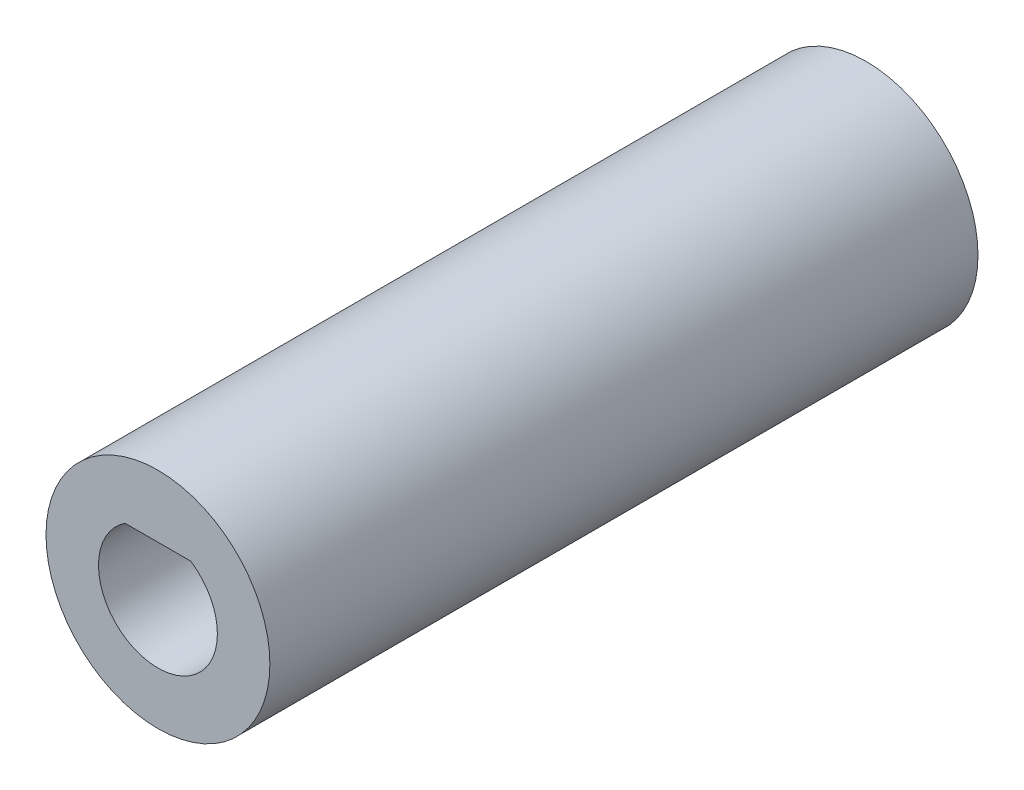
SolidWorks part; units mm, degrees
ref_plane "Front Plane" through (0, 0, 0) normal (0, 0, 1) x (1, 0, 0)
ref_plane "Top Plane" through (0, 0, 0) normal (0, 1, 0) x (1, 0, 0)
ref_plane "Right Plane" through (0, 0, 0) normal (1, 0, 0) x (0, 0, -1)
sketch "Sketch1" plane through (0, 0, 0) normal (0, 0, 1) x (1, 0, 0)
  circle A0 centre (0, 0) radius 3.65 construction
  circle A1 centre (0, 0) radius 5.65
  circle A2 centre (0, 0) radius 1.55
  circle A3 centre (0, 0) radius 3.65 construction
  arc A4 (-1.2776, -2.7957) -> (-1.2728, -2.7489) centre (-1.7505, -2.7239) ccw
  arc A5 (-0.4154, -3.0006) -> (-0.4367, -3.0426) centre (0, -3.2379) ccw
  arc A6 (0.4154, -3.0006) -> (-0.4154, -3.0006) centre (0, -3.2379) ccw
  arc A7 (0.4367, -3.0426) -> (0.4154, -3.0006) centre (0, -3.2379) ccw
  arc A8 (1.2728, -2.7489) -> (1.2776, -2.7957) centre (1.7505, -2.7239) ccw
  arc A9 (2.0123, -2.3235) -> (1.9717, -2.2997) centre (1.7505, -2.7239) ccw
  arc A10 (2.9491, -0.8667) -> (2.902, -0.8686) centre (2.9453, -1.3451) ccw
  arc A11 (2.5569, -1.6244) -> (2.5862, -1.6612) centre (2.9453, -1.3451) ccw
  arc A12 (3.0292, 0.0158) -> (3.0738, 0.0007) centre (3.2049, 0.4608) ccw
  arc A13 (2.9495, 0.8653) -> (2.911, 0.8382) centre (3.2049, 0.4608) ccw
  arc A14 (2.9491, -0.8667) -> (3.5766, -0.7323) centre (2.9608, 0.6111) ccw
  arc A15 (2.902, -0.8686) -> (2.5569, -1.6244) centre (2.9453, -1.3451) ccw
  arc A16 (2.8956, -2.2234) -> (2.5862, -1.6612) centre (1.4771, -2.6378) ccw
  arc A17 (2.6129, -2.5497) -> (2.8956, -2.2234) centre (0, 0) ccw
  arc A18 (2.0123, -2.3235) -> (2.6129, -2.5497) centre (2.8211, -1.0866) ccw
  arc A19 (1.9717, -2.2997) -> (1.2728, -2.7489) centre (1.7505, -2.7239) ccw
  arc A20 (1.2339, -3.436) -> (1.2776, -2.7957) centre (-0.1835, -3.0176) ccw
  arc A21 (0.8196, -3.5576) -> (1.2339, -3.436) centre (0, 0) ccw
  arc A22 (0.4367, -3.0426) -> (0.8196, -3.5576) centre (1.7858, -2.4394) ccw
  arc A23 (-0.8196, -3.5576) -> (-0.4367, -3.0426) centre (-1.7858, -2.4394) ccw
  arc A24 (-1.2339, -3.436) -> (-0.8196, -3.5576) centre (0, 0) ccw
  arc A25 (-1.2776, -2.7957) -> (-1.2339, -3.436) centre (0.1835, -3.0176) ccw
  arc A26 (3.5766, -0.7323) -> (3.638, -0.305) centre (0, 0) ccw
  arc A27 (3.638, -0.305) -> (3.0738, 0.0007) centre (2.6687, -1.4205) ccw
  arc A28 (2.911, 0.8382) -> (3.0292, 0.0158) centre (3.2049, 0.4608) ccw
  arc A29 (2.9495, 0.8653) -> (3.4047, 1.3176) centre (2.1604, 2.1148) ccw
  arc A30 (3.4047, 1.3176) -> (3.2254, 1.7103) centre (0, 0) ccw
  arc A31 (-1.9717, -2.2997) -> (-2.0123, -2.3235) centre (-1.7505, -2.7239) ccw
  arc A32 (-2.5862, -1.6612) -> (-2.5569, -1.6244) centre (-2.9453, -1.3451) ccw
  arc A33 (-2.902, -0.8686) -> (-2.9491, -0.8667) centre (-2.9453, -1.3451) ccw
  arc A34 (-3.0738, 0.0007) -> (-3.0292, 0.0158) centre (-3.2049, 0.4608) ccw
  arc A35 (-2.911, 0.8382) -> (-2.9495, 0.8653) centre (-3.2049, 0.4608) ccw
  arc A36 (-1.2728, -2.7489) -> (-1.9717, -2.2997) centre (-1.7505, -2.7239) ccw
  arc A37 (-2.6129, -2.5497) -> (-2.0123, -2.3235) centre (-2.8211, -1.0866) ccw
  arc A38 (-2.8956, -2.2234) -> (-2.6129, -2.5497) centre (0, 0) ccw
  arc A39 (-2.5862, -1.6612) -> (-2.8956, -2.2234) centre (-1.4771, -2.6378) ccw
  arc A40 (-2.5569, -1.6244) -> (-2.902, -0.8686) centre (-2.9453, -1.3451) ccw
  arc A41 (-3.5766, -0.7323) -> (-2.9491, -0.8667) centre (-2.9608, 0.6111) ccw
  arc A42 (-3.638, -0.305) -> (-3.5766, -0.7323) centre (0, 0) ccw
  arc A43 (-3.0738, 0.0007) -> (-3.638, -0.305) centre (-2.6687, -1.4205) ccw
  arc A44 (-3.0292, 0.0158) -> (-2.911, 0.8382) centre (-3.2049, 0.4608) ccw
  arc A45 (-3.4047, 1.3176) -> (-2.9495, 0.8653) centre (-2.1604, 2.1148) ccw
  arc A46 (-2.5854, 1.6624) -> (-2.5398, 1.651) centre (-2.447, 2.1203) ccw
  arc A47 (-1.9957, 2.279) -> (-2.0134, 2.3225) centre (-2.447, 2.1203) ccw
  arc A48 (-1.2762, 2.7963) -> (-1.244, 2.762) centre (-0.9122, 3.1067) ccw
  arc A49 (-0.4468, 2.9961) -> (-0.4382, 3.0424) centre (-0.9122, 3.1067) ccw
  arc A50 (2.5398, 1.651) -> (2.5854, 1.6624) centre (2.447, 2.1203) ccw
  arc A51 (2.0134, 2.3225) -> (1.9957, 2.279) centre (2.447, 2.1203) ccw
  arc A52 (3.2254, 1.7103) -> (2.5854, 1.6624) centre (3.013, 0.2478) ccw
  arc A53 (1.9957, 2.279) -> (2.5398, 1.651) centre (2.447, 2.1203) ccw
  arc A54 (2.0134, 2.3225) -> (2.1519, 2.9492) centre (0.6741, 2.9471) ccw
  arc A55 (2.1519, 2.9492) -> (1.7887, 3.1826) centre (0, 0) ccw
  arc A56 (1.244, 2.762) -> (1.2762, 2.7963) centre (0.9122, 3.1067) ccw
  arc A57 (0.4382, 3.0424) -> (0.4468, 2.9961) centre (0.9122, 3.1067) ccw
  arc A58 (1.7887, 3.1826) -> (1.2762, 2.7963) centre (2.4007, 1.8374) ccw
  arc A59 (0.4468, 2.9961) -> (1.244, 2.762) centre (0.9122, 3.1067) ccw
  arc A60 (0.4382, 3.0424) -> (0.2158, 3.6444) centre (-1.0262, 2.8437) ccw
  arc A61 (0.2158, 3.6444) -> (0, 3.6508) centre (0, 0) ccw
  arc A62 (0, 3.6508) -> (-0.2158, 3.6444) centre (0, 0) ccw
  arc A63 (-0.2158, 3.6444) -> (-0.4382, 3.0424) centre (1.0262, 2.8437) ccw
  arc A64 (-1.244, 2.762) -> (-0.4468, 2.9961) centre (-0.9122, 3.1067) ccw
  arc A65 (-1.2762, 2.7963) -> (-1.7887, 3.1826) centre (-2.4007, 1.8374) ccw
  arc A66 (-1.7887, 3.1826) -> (-2.1519, 2.9492) centre (0, 0) ccw
  arc A67 (-2.1519, 2.9492) -> (-2.0134, 2.3225) centre (-0.6741, 2.9471) ccw
  arc A68 (-2.5398, 1.651) -> (-1.9957, 2.279) centre (-2.447, 2.1203) ccw
  arc A69 (-2.5854, 1.6624) -> (-3.2254, 1.7103) centre (-3.013, 0.2478) ccw
  arc A70 (-3.2254, 1.7103) -> (-3.4047, 1.3176) centre (0, 0) ccw
  circle A71 centre (0, 0) radius 3.6508
  point P4 (0, 3.65)
  point P9 (0, 5.65)
  dimension "D3" = 7.3
extrude "Boss-Extrude1" add sketch "Sketch1" along normal blind 7 contours A1 A71 A30 A26 A17 A21 A24 A38 A42 A70 A66 A62 A61 A55 | A67 A71 A69 A46 A68 A47 | A63 A71 A65 A48 A64 A49 | A58 A71 A60 A57 A59 A56 | A52 A71 A54 A51 A53 A50 | A27 A71 A29 A13 A28 A12 | A16 A71 A14 A10 A15 A11 | A20 A71 A18 A9 A19 A8 | A23 A71 A22 A7 A6 A5 | A37 A71 A25 A4 A36 A31 | A41 A71 A39 A32 A40 A33 | A45 A71 A43 A34 A44 A35
sketch "Sketch2" plane through (0, 0, 7) normal (0, 0, 1) x (1, 0, 0)
  circle A0 centre (0, 0) radius 5.65
extrude "Boss-Extrude2" add sketch "Sketch2" along normal blind 14.74
sketch "Sketch3" plane through (0, 0, 21.74) normal (0, 0, 1) x (1, 0, 0)
  line L0 (-1.6583, 2.5) -> (1.6583, 2.5)
  circle A0 centre (0, 0) radius 3 construction
  circle A1 centre (0, 0) radius 5.65
  arc A2 (-1.6583, 2.5) -> (1.6583, 2.5) centre (0, 0) ccw
  point P5 (0, 2.5)
  dimension "D1" = 6
  dimension "D2" = 2.5
extrude "Boss-Extrude3" add sketch "Sketch3" along normal blind 14 contours L0 A2
